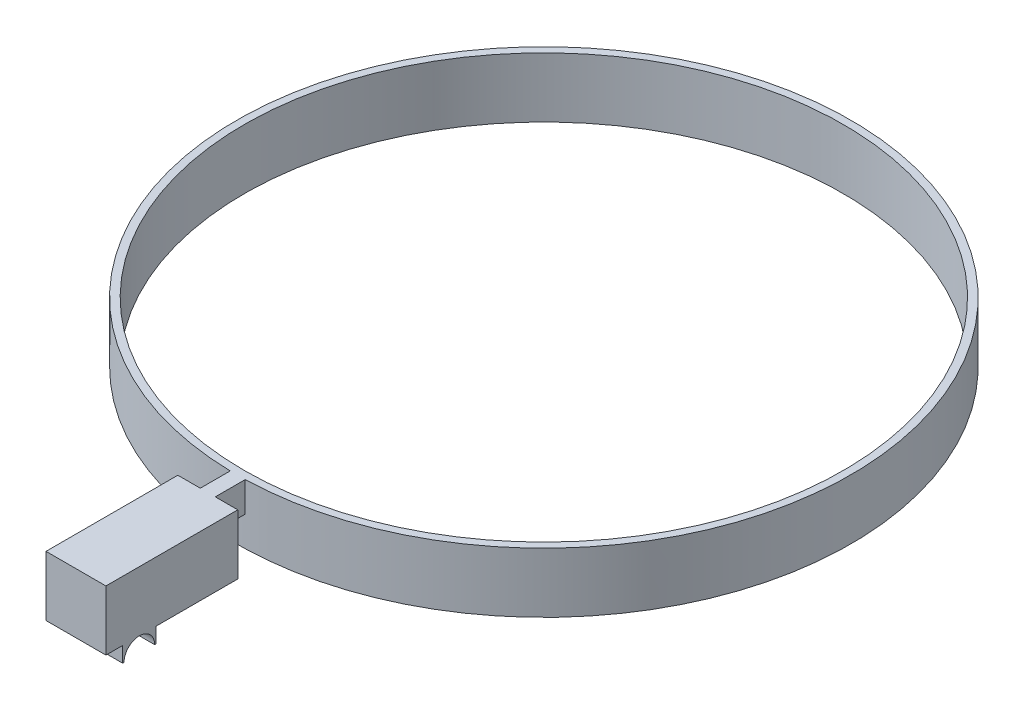
SolidWorks part; units mm, degrees
ref_plane "Front Plane" through (0, 0, 0) normal (0, 0, 1) x (1, 0, 0)
ref_plane "Top Plane" through (0, 0, 0) normal (0, 1, 0) x (1, 0, 0)
ref_plane "Right Plane" through (0, 0, 0) normal (1, 0, 0) x (0, 0, -1)
sketch "Sketch1" plane through (0, 0, 0) normal (0, 1, 0) x (1, 0, 0)
  circle A0 centre (0, 0) radius 100
  circle A1 centre (0, 0) radius 102.5
  dimension "D1" = 200
  dimension "D2" = 205
extrude "Boss-Extrude1" add sketch "Sketch1" along normal blind 20
sketch "Sketch2" plane through (0, 20, 0) normal (0, 1, 0) x (1, 0, 0)
  line L0 (0, -102.5) -> (0, 0) construction
  line L1 (-2.2014, -102.4764) -> (-2.2014, -112.4618)
  line L2 (-2.2014, -112.4618) -> (2.7986, -112.4618)
  line L3 (2.7986, -112.4618) -> (2.7986, -102.4618)
  line L4 (2.7986, -102.4618) -> (-2.2014, -102.4764)
  circle A1 centre (0, 0) radius 102.5
  arc A2 (-2.2014, -102.4764) -> (2.7986, -102.4618) centre (0, 0) ccw
  circle M7 centre (0, 0) radius 102.5
  dimension "D2" = 10
  dimension "D3" = 5
  dimension "D1" = 0
extrude "Boss-Extrude2" add sketch "Sketch2" against normal blind 10 contours L2 L3 A2 L1 M7
sketch "Sketch3" plane through (0, 0, 112.4618) normal (0, 0, 1) x (1, 0, 0)
  line L0 (-2.2014, 20) -> (2.7986, 20) construction
  line L2 (-9.7014, 20) -> (-9.7014, 0)
  line L3 (-9.7014, 0) -> (10.2986, 0)
  line L4 (10.2986, 20) -> (10.2986, 0)
  line L5 (0.2986, 20) -> (10.2986, 0) construction
  line L6 (-9.7014, 0) -> (0.2986, 20) construction
  line L7 (-9.7014, 20) -> (10.2986, 20)
  point P0 (0.2986, 20)
  dimension "D1" = 20
  dimension "D2" = 20
  dimension "D3" = 20
  dimension "D4" = 10
extrude "Boss-Extrude3" add sketch "Sketch3" along normal blind 44
sketch "Sketch4" plane through (-9.7014, 0, 0) normal (-1, 0, 0) x (0, 0, 1)
  line L1 (139.7118, 0) -> (139.7118, -5.1)
  line L2 (156.4618, 0) -> (112.4618, 0) construction
  line L3 (139.7118, -5.1) -> (140.2118, -5.1)
  line L5 (150.4118, -5.1) -> (150.9118, -5.1)
  line L6 (150.9118, -5.1) -> (150.9118, 0)
  line L7 (150.9118, 0) -> (139.7118, 0)
  arc A1 (150.4118, -5.1) -> (140.2118, -5.1) centre (145.3118, -5.1) ccw
  point P1 (145.3118, 0)
  line M9 (112.4618, 0) -> (156.4618, 0)
  dimension "D1" = 5.1
  dimension "D2" = 5.1
  dimension "D3" = 0.5
  dimension "D4" = 0.5
  dimension "D5" = 11.2
  dimension "D6" = 11.15
extrude "Boss-Extrude5" add sketch "Sketch4" against normal blind 20 contours A1 L1 L3 M9 | A1 L5 L6 L7
